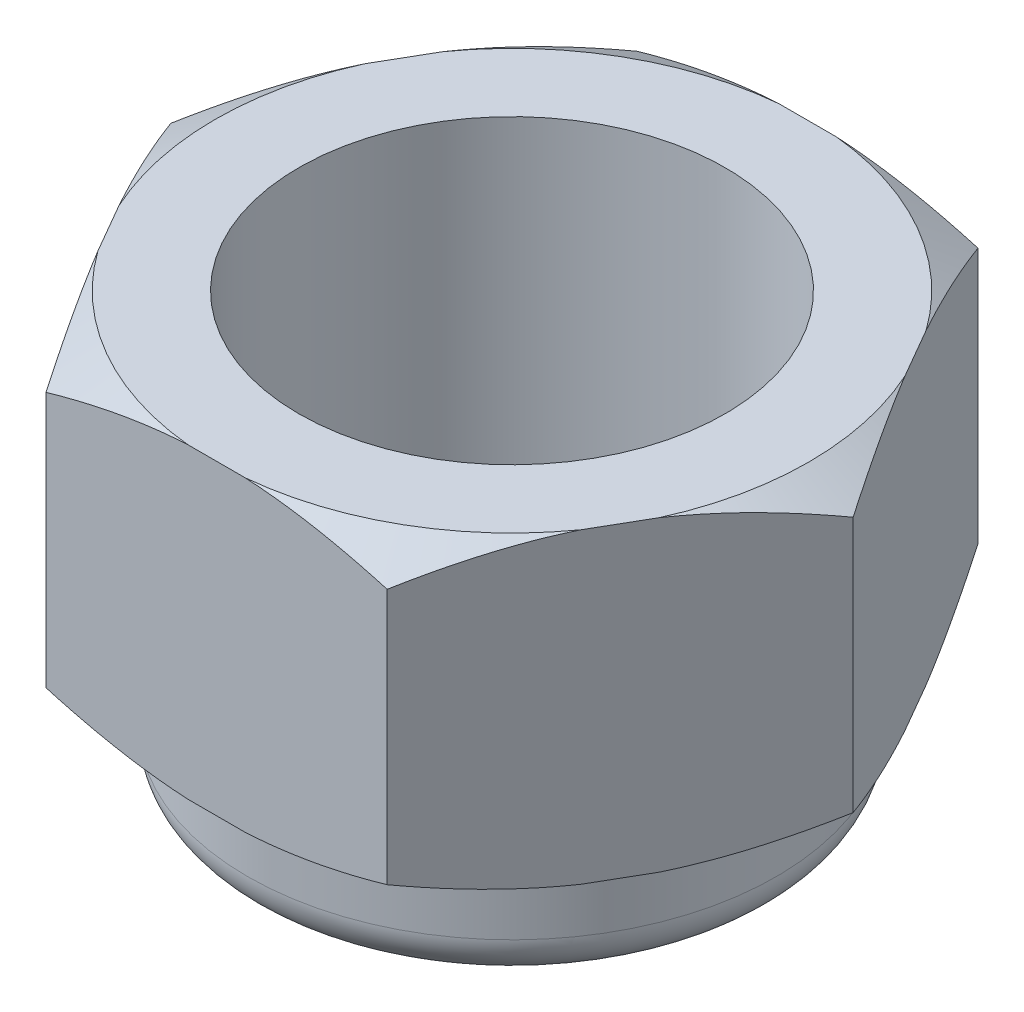
SolidWorks part; units mm, degrees
ref_plane "前视基准面" through (0, 0, 0) normal (0, 0, 1) x (1, 0, 0)
ref_plane "上视基准面" through (0, 0, 0) normal (0, 1, 0) x (1, 0, 0)
ref_plane "右视基准面" through (0, 0, 0) normal (1, 0, 0) x (0, 0, -1)
other "Configuration Table"
sketch "草图1" plane through (0, 0, 0) normal (0, 1, 0) x (1, 0, 0)
  line L0 (4, 0) -> (0, 0) construction
  line L1 (4, 0) -> (2, 3.4641)
  line L2 (2, 3.4641) -> (-2, 3.4641)
  line L3 (-2, 3.4641) -> (-4, 0)
  line L4 (-4, 0) -> (-2, -3.4641)
  line L5 (-2, -3.4641) -> (2, -3.4641)
  line L6 (2, -3.4641) -> (4, 0)
  circle A0 centre (0, 0) radius 3.4641 construction
  circle A1 centre (0, 0) radius 2.5
  dimension "D2" = 5
  dimension "D1" = 8
extrude "凸台-拉伸1" add sketch "草图1" along normal blind 3.6
sketch "草图3" plane through (0, 0, 0) normal (1, 0, 0) x (0, 0, -1)
  line L0 (0, 0) -> (0, 6.4295) construction
ref_plane "基准面1" through (0, 0, 0) normal (-0.866, 0, -0.5) x (-0.5, 0, 0.866)
sketch "草图4" plane through (0, 0, 0) normal (-0.866, 0, -0.5) x (-0.5, 0, 0.866)
  line L0 (0, 5.6094) -> (-4, 3.3)
  line L1 (0, 0) -> (0, 6.4295) construction
  line L2 (-4, 3.3) -> (-4, 5.6637)
  line L4 (-4, 3.6) -> (-4, 0) construction
  line L5 (-4, 3.6) -> (-2, 3.6) construction
  line L6 (-4, 5.6637) -> (-4, 6.1094)
  line L7 (-4, 6.1094) -> (0, 6.1094)
  line L8 (0, 6.1094) -> (0, 5.6094)
  line L9 (0, 6.1094) -> (0, 7.0465) construction
  line L10 (-5.6043, 1.8) -> (5.271, 1.8) construction
  line L11 (-2, 0) -> (2, 0) construction
  line L12 (-2, 3.6) -> (2, 3.6) construction
  line L13 (0, -2.5094) -> (0, -3.4465) construction
  line L14 (0, -2.5094) -> (0, -2.0094)
  line L15 (-4, -2.5094) -> (0, -2.5094)
  line L16 (-4, -2.0637) -> (-4, -2.5094)
  line L17 (-4, 0.3) -> (-4, -2.0637)
  line L18 (0, -2.0094) -> (-4, 0.3)
  dimension "D1" = 60
  dimension "D2" = 0.3
  dimension "D3" = 0.4457
  dimension "D4" = 0.5
revolve "切除-旋转1" cut sketch "草图4" angle 360 about L9
sketch "草图2" plane through (0, 3.6, 0) normal (0, 1, 0) x (1, 0, 0)
  circle A0 centre (0, 0) radius 3.1
  circle A1 centre (0, 0) radius 2.5 construction
  circle A2 centre (0, 0) radius 2.5
  dimension "D1" = 0.6
extrude "凸台-拉伸2" add sketch "草图2" against normal blind 4.9
fillet "圆角1" radius 0.5 1 edges at (0, -1.3, 3.1)
